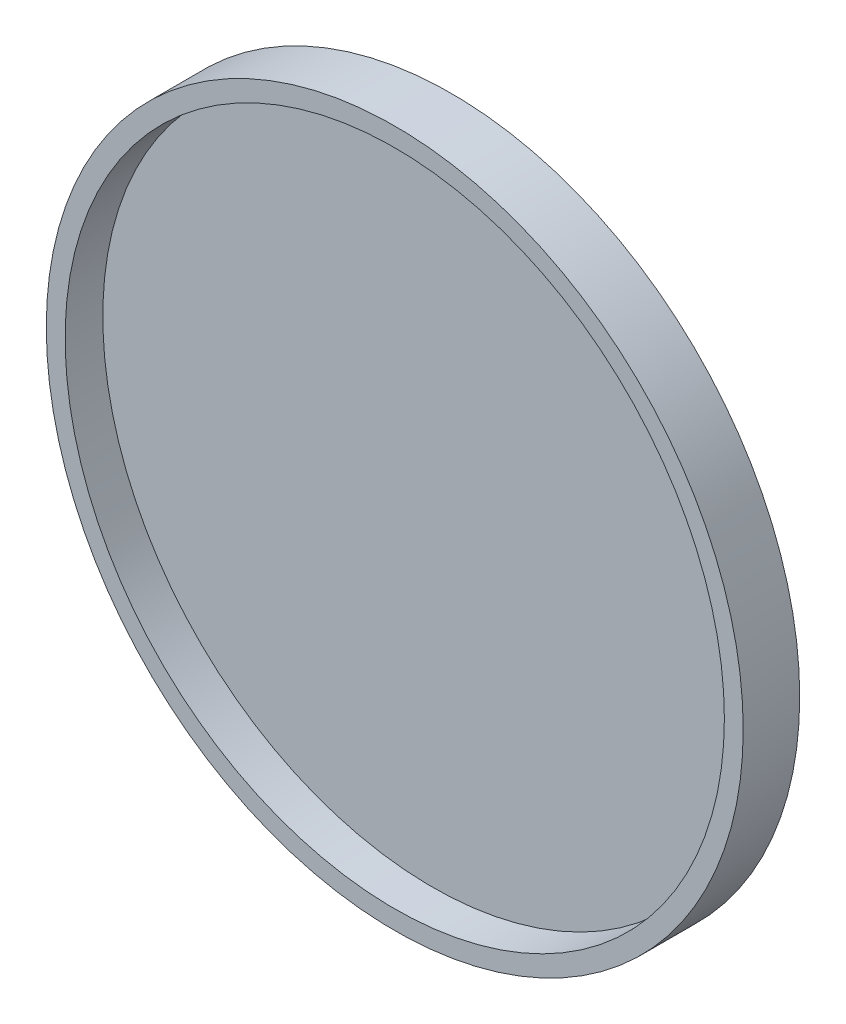
SolidWorks part; units mm, degrees
ref_plane "Plan de face" through (0, 0, 0) normal (0, 0, 1) x (1, 0, 0)
ref_plane "Plan de dessus" through (0, 0, 0) normal (0, 1, 0) x (1, 0, 0)
ref_plane "Plan de droite" through (0, 0, 0) normal (1, 0, 0) x (0, 0, -1)
sketch "Esquisse1" plane through (0, 0, 0) normal (0, 0, 1) x (1, 0, 0)
  circle A0 centre (0, 0) radius 37
  dimension "D1" = 74
extrude "Boss.-Extru.1" add sketch "Esquisse1" along normal blind 6
sketch "Esquisse2" plane through (0, 0, 6) normal (0, 0, 1) x (1, 0, 0)
  circle A0 centre (0, 0) radius 35
  dimension "D1" = 70
extrude "Enlèv. mat.-Extru.1" cut sketch "Esquisse2" against normal blind 4
